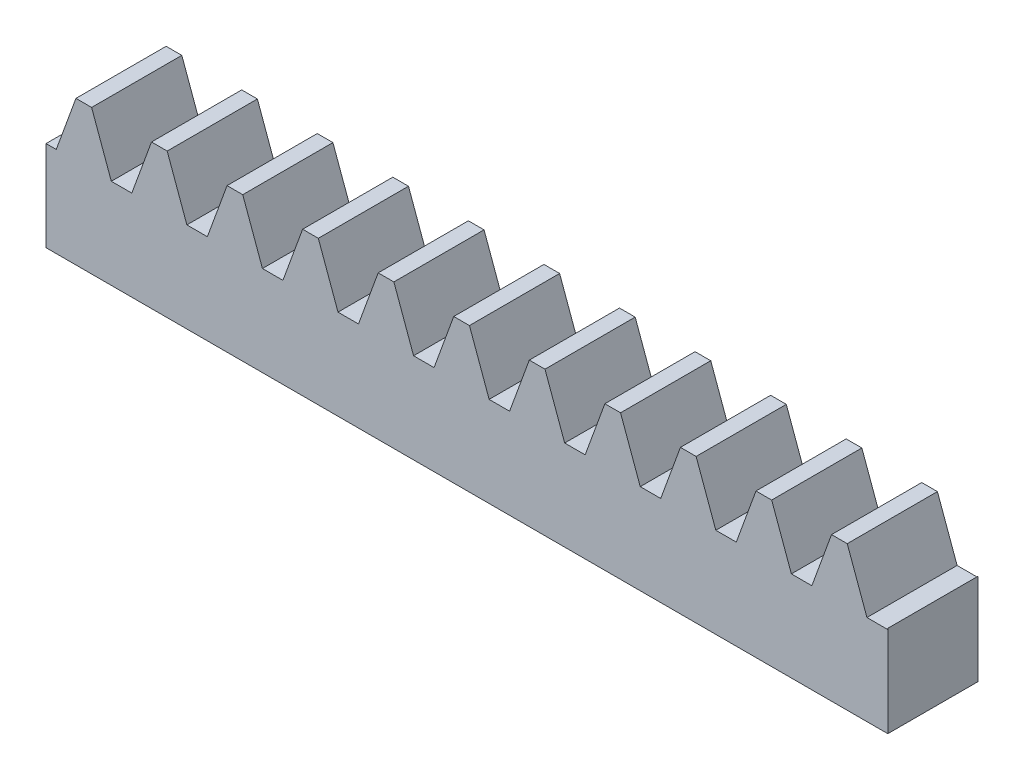
SolidWorks part; units mm, degrees
extrude "Blank" add sketch "BlankSke" against normal blind 15
sketch "BlankSke" plane through (0, 0, 0) normal (0, 0, 1) x (1, 0, 0)
  line L1 (0, 0) -> (140, 0)
  line L2 (0, 0) -> (0, 24)
  line L3 (0, 24) -> (140, 24)
  line L4 (140, 0) -> (140, 24)
  dimension "Length" = 140
  dimension "Blank_height" = 24
ref_plane "Plane1" through (0, 0, 0) normal (0, 0, 1) x (1, 0, 0)
ref_plane "Plane2" through (0, 0, 0) normal (0, 1, 0) x (1, 0, 0)
ref_plane "Plane3" through (0, 0, 0) normal (1, 0, 0) x (0, 0, -1)
other "Configuration Table"
sketch "HoldingSke" plane through (0, 0, 0) normal (0, 1, 0) x (1, 0, 0)
  line L0 (0, 0) -> (0.0348, 0.2476)
  line L1 (-15, 0) -> (100, 0) construction
  line L2 (0, 0) -> (-2.1039, 2.3779)
  line L3 (0, 0) -> (-11.863, 4.5341)
  line L4 (0, 0) -> (8.4147, 1.9427)
  line L5 (0, 0) -> (-23.7986, -8.8762)
  line L6 (0, 0) -> (-10.5278, -7.1032)
  line L9 (-71.009, 38.7566) -> (60.548, 86.6394)
  line L10 (-76.2, 6.3779) -> (-56.2, 6.3779)
  line L11 (0, 0) -> (-15, 0)
  line L12 (-76.2, 101.6) -> (-76.073, 101.6)
  line L13 (24.9733, 27.94) -> (52.9518, 28.4284)
  line L14 (24.9733, 27.94) -> (24.9743, 27.94)
  line L15 (24.9733, 27.94) -> (100.4006, 29.5858)
  circle A0 centre (0, 0) radius 19.05
  circle A1 centre (0, 0) radius 10
  circle A2 centre (0, 0) radius 12.7
  dimension "MPH" = 20
  dimension "Diameter" = 38.1
  dimension "Num_teeth" = 13
  dimension "Pitch" = 0.25
  dimension "Show_teeth" = 998
  dimension "Thickness" = 12.7
  dimension "Ap" = 20
  dimension "Pitch_height" = 20
  dimension "Width" = 15
  dimension "Backlash" = 0.127
  dimension "Addendum_fac" = 1
  dimension "Dedendum_fac" = 1.25
  dimension "Clearance_fac" = 0.25
  dimension "Dedendum_add" = 0.001
  dimension "Length" = 140
  dimension "Module" = 4
sketch "TooCutSkeIll" plane through (0, 0, 0) normal (0, 0, 1) x (1, 0, 0)
  line L0 (-4.9402, 23.8947) -> (-1.9425, 15.6586)
  line L1 (-1.0018, 15) -> (1.0018, 15)
  line L2 (1.9425, 15.6586) -> (4.9402, 23.8947)
  line L3 (140, 24) -> (0, 24) construction
  line L4 (0, 0) -> (0, 64.897) construction
  line L5 (-13.208, 20) -> (12.954, 20) construction
  line L6 (0, 0) -> (140, 0) construction
  line L7 (3.5226, 20) -> (3.5226, 48.7463) construction
  line L8 (-3.5226, 20) -> (-3.5226, 48.7463) construction
  line L9 (5.0905, 24) -> (5.0905, 24.0254)
  line L10 (-5.0905, 24) -> (-5.0905, 24.0254)
  line L11 (-5.0905, 24.0254) -> (5.0905, 24.0254)
  arc A0 (1.0018, 15) -> (1.9425, 15.6586) centre (1.0018, 16.001) ccw
  arc A1 (-1.9425, 15.6586) -> (-1.0018, 15) centre (-1.0018, 16.001) ccw
  arc A2 (5.0905, 24) -> (4.9402, 23.8947) centre (5.0905, 23.84) ccw
  arc A3 (-4.9402, 23.8947) -> (-5.0905, 24) centre (-5.0905, 23.84) ccw
  dimension "Pitch_height" = 20
  dimension "Addendum_plus" = 4.0254
  dimension "Pressure_angle" = 20
  dimension "Gap_width" = 7.0452
  dimension "Dedendum" = 5
extrude "ToothCutIll" [suppressed] cut sketch "TooCutSkeIll" against normal through all
sketch "TooCutSkeSim" plane through (0, 0, 0) normal (0, 0, 1) x (1, 0, 0)
  line L0 (1.7027, 15) -> (-1.7027, 15)
  line L1 (4.9877, 24.0254) -> (1.7027, 15)
  line L2 (0, 17.4625) -> (0, 53.467) construction
  line L3 (4.9877, 24.0254) -> (-4.9877, 24.0254)
  line L6 (-4.9877, 24.0254) -> (-1.7027, 15)
  line L9 (-3.5226, 20) -> (3.5226, 20) construction
  line L10 (0, 0) -> (140, 0) construction
  line L11 (3.5226, 20) -> (3.5226, 53.467) construction
  line L12 (-3.5226, 20) -> (-3.5226, 53.467) construction
  dimension "Pitch_height" = 20
  dimension "Addendum_plus" = 4.0254
  dimension "Pressure_angle" = 20
  dimension "Gap_width" = 7.0452
  dimension "Dedendum" = 5
extrude "ToothCutSim" cut sketch "TooCutSkeSim" against normal through all
pattern_linear "TeethCuts" count 12 spacing 12.5664 along (1, 0, 0) of "ToothCutIll", "ToothCutSim"
equation "' \"Module@HoldingSke\" = 6.35"
equation "' \"Num_teeth@HoldingSke\" = 12"
equation "' \"Ap@HoldingSke\" =  20"
equation "' \"Ap@HoldingSke\" = 20"
equation "' \"Width@HoldingSke\" = 0.25 * 25.4"
equation "' \"Show_teeth@HoldingSke\" = 500"
equation "' \"Backlash@HoldingSke\" = 0.009 * 25.4"
equation "' \"Addendum_fac@HoldingSke\" = 1.0"
equation "' \"Dedendum_fac@HoldingSke\" = 1.25"
equation "' \"Dedendum_add@HoldingSke\" = 0.00005 * 25.4"
equation "' \"Clearance_fac@HoldingSke\" = 0.25"
equation "' \"Pitch_height@HoldingSke\" = 1 * 25.4"
equation "' \"Length@HoldingSke\" = 4.71 * 25.4"
equation "\"Pitch@HoldingSke\" = 1 / \"Module@HoldingSke\""
equation "\"MPH@HoldingSke\" = \"Dedendum_fac@HoldingSke\" / \"Pitch@HoldingSke\" + 2 * \"Dedendum_add@HoldingSke\" + 0.002 * 25.4"
equation "\"MPH@HoldingSke\" = ((sgn( \"MPH@HoldingSke\" - \"Pitch_height@HoldingSke\")+1)*( \"MPH@HoldingSke\" - \"Pitch_height@HoldingSke\"))/2 + \"Pitch_height@HoldingSke\""
equation "\"Blank_height@BlankSke\" = \"Pitch_height@HoldingSke\" + \"Addendum_fac@HoldingSke\"  / \"Pitch@HoldingSke\" "
equation "\"Length@BlankSke\" =  \"Length@HoldingSke\""
equation "\"Face_width@Blank\" = \"Width@HoldingSke\""
equation "\"Pressure_angle@TooCutSkeIll\" = \"Ap@HoldingSke\""
equation "\"Addendum_plus@TooCutSkeIll\" =  \"Addendum_fac@HoldingSke\"  / \"Pitch@HoldingSke\" + 0.001 *25.4"
equation "\"Dedendum@TooCutSkeIll\" = \"Dedendum_fac@HoldingSke\"  / \"Pitch@HoldingSke\""
equation "\"Pitch_height@TooCutSkeIll\" =  \"MPH@HoldingSke\""
equation "\"Gap_width@TooCutSkeIll\" = 3.14159265 / 2 / \"Pitch@HoldingSke\" + 6 * \"Backlash@HoldingSke\""
equation "\"Pressure_angle@TooCutSkeSim\" = \"Ap@HoldingSke\""
equation "\"Addendum_plus@TooCutSkeSim\" =  \"Addendum_fac@HoldingSke\"  / \"Pitch@HoldingSke\" + 0.001 * 25.4"
equation "\"Dedendum@TooCutSkeSim\" = \"Dedendum_fac@HoldingSke\"  / \"Pitch@HoldingSke\""
equation "\"Pitch_height@TooCutSkeSim\" =  \"MPH@HoldingSke\""
equation "\"Gap_width@TooCutSkeSim\" = 3.14159265 / 2 / \"Pitch@HoldingSke\" + 6 * \"Backlash@HoldingSke\""
equation "\"Root_fillet@TooCutSkeIll\" = \"Clearance_fac@HoldingSke\" / \"Pitch@HoldingSke\" + \"Dedendum_add@HoldingSke\""
equation "\"Break_rad@TooCutSkeIll\" = 0.02 / \"Pitch@HoldingSke\" * 2"
equation "\"Linear_pitch@TeethCuts\" = 3.14159265 / \"Pitch@HoldingSke\""
equation "\"Num_teeth@HoldingSke\" = int( ( \"Length@HoldingSke\" + 0 ) / (3.14159265 / \"Pitch@HoldingSke\")) + 0.9999  + 1"
equation " \"Num_teeth@TeethCuts\" = int( \"Show_teeth@HoldingSke\" ) + 1"
equation " \"Num_teeth@TeethCuts\" = ((sgn( \"Num_teeth@TeethCuts\" - \"Num_teeth@HoldingSke\" )-1)*( \"Num_teeth@TeethCuts\" - \"Num_teeth@HoldingSke\" ))/-2+ \"Num_teeth@HoldingSke\""
equation " \"Num_teeth@TeethCuts\" = ((sgn( \"Num_teeth@TeethCuts\" - 2.0)+1)*( \"Num_teeth@TeethCuts\" - 2.0))/2 +2.0"
